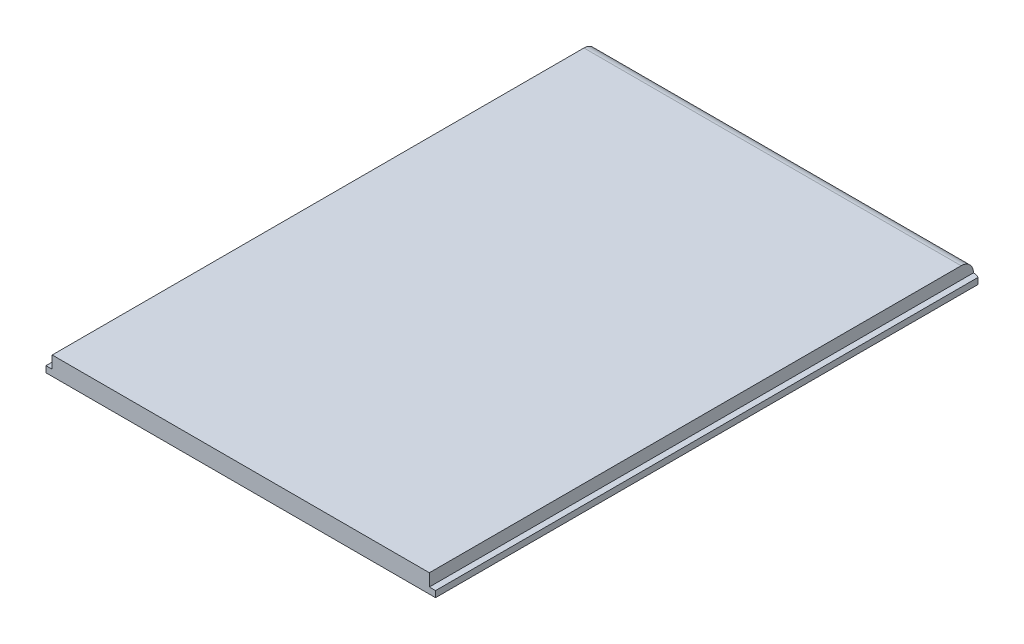
SolidWorks part; units mm, degrees
ref_plane "Front Plane" through (0, 0, 0) normal (0, 0, 1) x (1, 0, 0)
ref_plane "Top Plane" through (0, 0, 0) normal (0, 1, 0) x (1, 0, 0)
ref_plane "Right Plane" through (0, 0, 0) normal (1, 0, 0) x (0, 0, -1)
sketch "Sketch2" plane through (0, 0, 0) normal (0, 1, 0) x (1, 0, 0)
  line L1 (-38.735, -55.88) -> (38.735, -55.88)
  line L2 (-38.735, -55.88) -> (-38.735, 55.88)
  line L3 (-38.735, 55.88) -> (38.735, 55.88)
  line L4 (38.735, -55.88) -> (38.735, 55.88)
  line L5 (-38.735, -55.88) -> (38.735, 55.88) construction
  line L6 (-38.735, 55.88) -> (38.735, -55.88) construction
  point P0 (0, 0)
  dimension "D1" = 77.47
  dimension "D2" = 111.76
extrude "Boss-Extrude1" add sketch "Sketch2" along normal blind 3.81
sketch "Sketch3" plane through (0, 0, 55.88) normal (0, 0, 1) x (1, 0, 0)
  line L0 (-38.735, 3.81) -> (-38.735, 0) construction
  line L1 (-38.735, 1.27) -> (-40.005, 1.27)
  line L2 (-38.735, 1.27) -> (-38.735, 0)
  line L3 (-38.735, 0) -> (-40.005, 0)
  line L4 (-40.005, 1.27) -> (-40.005, 0)
  line L6 (-38.735, 0) -> (38.735, 0) construction
  line L7 (0, 0) -> (0, 3.81) construction
  line L8 (-38.735, 3.81) -> (38.735, 3.81) construction
  line L9 (40.005, 1.27) -> (40.005, 0)
  line L10 (38.735, 0) -> (40.005, 0)
  line L11 (38.735, 1.27) -> (38.735, 0)
  line L12 (38.735, 1.27) -> (40.005, 1.27)
  dimension "D1" = 1.27
  dimension "D2" = 1.27
extrude "Boss-Extrude2" add sketch "Sketch3" against normal up to surface (111.76 mm away) up to face at (0, 1.905, -55.88)
fillet "Fillet1" radius 2.54 1 edges at (0, 3.81, -55.88)
sketch "Sketch5" plane through (0, 3.81, 0) normal (0, 1, 0) x (1, 0, 0)
  line L0 (38.735, 53.34) -> (41.275, 53.34) construction
  line L1 (40.005, 55.88) -> (40.005, -55.88) construction
  line L2 (38.735, 55.88) -> (40.005, 55.88) construction
  line L3 (0, 53.34) -> (0, 55.88) construction
  line L4 (40.005, 55.88) -> (38.735, 55.88)
  line L5 (40.005, 55.88) -> (40.005, 53.34)
  line L6 (40.005, 53.34) -> (38.735, 53.34)
  line L7 (38.735, 55.88) -> (38.735, 53.34)
  line L8 (38.735, 53.34) -> (-38.735, 53.34) construction
  line L9 (-38.735, 55.88) -> (38.735, 55.88) construction
  line L10 (-38.735, 53.34) -> (-41.275, 53.34) construction
  line L11 (-38.735, 55.88) -> (-38.735, 53.34)
  line L12 (-40.005, 53.34) -> (-38.735, 53.34)
  line L13 (-40.005, 55.88) -> (-40.005, 53.34)
  line L14 (-40.005, 55.88) -> (-38.735, 55.88)
  circle A0 centre (38.735, 53.34) radius 2.54
  circle A1 centre (-38.735, 53.34) radius 2.54
  point P2 (40.005, 53.34)
  dimension "D1" = 5.08
extrude "Cut-Extrude1" cut sketch "Sketch5" against normal up to next contours A0 L5 L4 | L13 A1 L14
